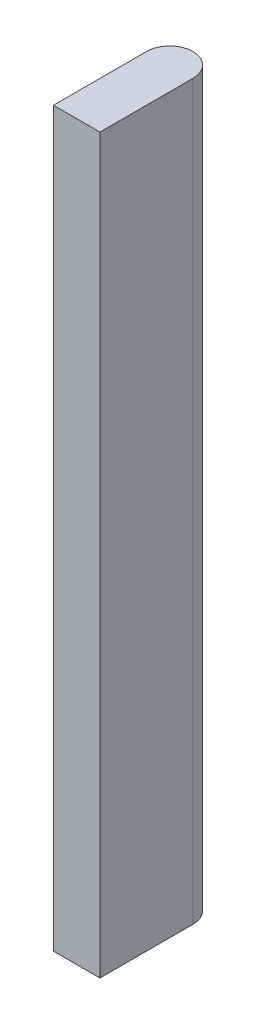
SolidWorks part; units mm, degrees
material "Alliage de zinc AC41A, brut"
ref_plane "Plan de face" through (0, 0, 0) normal (0, 0, 1) x (1, 0, 0)
ref_plane "Plan de dessus" through (0, 0, 0) normal (0, 1, 0) x (1, 0, 0)
ref_plane "Plan de droite" through (0, 0, 0) normal (1, 0, 0) x (0, 0, -1)
sketch "Esquisse1" plane through (0, 0, 0) normal (0, 1, 0) x (1, 0, 0)
  line L0 (0, 2.5) -> (0, -2.5) construction
  line L1 (-1, -2.5) -> (1, -2.5)
  line L2 (-1, -2.5) -> (-1, 1.5)
  line L4 (1, -2.5) -> (1, 1.5)
  arc A0 (1, 1.5) -> (-1, 1.5) centre (0, 1.5) ccw
  point P6 (0, -2.5)
  point P11 (0, 0)
  dimension "D1" = 1
  dimension "D2" = 4
extrude "Boss.-Extru.1" add sketch "Esquisse1" along normal blind 31.5
